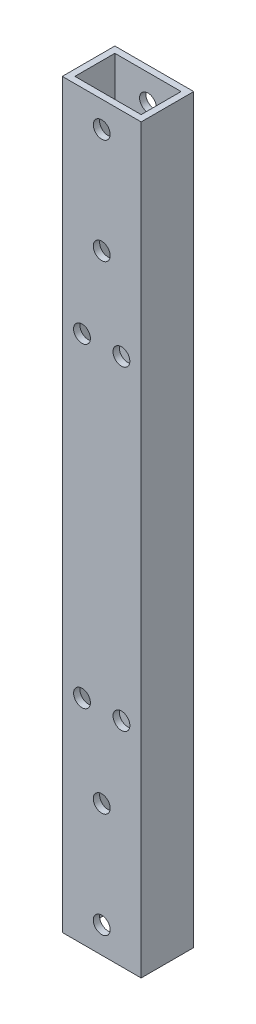
SolidWorks part; units mm, degrees
ref_plane "正面" through (0, 0, 0) normal (0, 0, 1) x (1, 0, 0)
ref_plane "平面" through (0, 0, 0) normal (0, 1, 0) x (1, 0, 0)
ref_plane "右側面" through (0, 0, 0) normal (1, 0, 0) x (0, 0, -1)
sketch "ｽｹｯﾁ1" plane through (0, 0, 0) normal (0, 1, 0) x (1, 0, 0)
  line L0 (-6.3, 3.8) -> (6.3, 3.8)
  line L1 (-7.5, 5) -> (7.5, 5)
  line L2 (-7.5, 5) -> (-7.5, -5)
  line L3 (-7.5, -5) -> (7.5, -5)
  line L4 (7.5, 5) -> (7.5, -5)
  line L5 (-7.5, 5) -> (7.5, -5) construction
  line L6 (-7.5, -5) -> (7.5, 5) construction
  line L7 (6.3, 3.8) -> (6.3, -3.8)
  line L8 (-6.3, -3.8) -> (6.3, -3.8)
  line L9 (-6.3, 3.8) -> (-6.3, -3.8)
  point P0 (0, 0)
  dimension "D1" = 15
  dimension "D2" = 10
  dimension "D3" = 1.2
extrude "ﾎﾞｽ - 押し出し1" add sketch "ｽｹｯﾁ1" along normal mid plane 141
sketch "ｽｹｯﾁ2" plane through (0, 0, -5) normal (0, 0, -1) x (-1, 0, 0)
  line L0 (0, 0) -> (-7.5, 0) construction
  line L1 (-7.5, 70.5) -> (-7.5, -70.5) construction
  line L2 (0, 0) -> (0, -70.5) construction
  line L3 (-7.5, -70.5) -> (7.5, -70.5) construction
  line L4 (0, 0) -> (0, -30) construction
  line L5 (0, -30) -> (7.5, -30) construction
  line L6 (7.5, 70.5) -> (7.5, -70.5) construction
  circle A0 centre (0, -65.5) radius 1.6
  circle A1 centre (0, -45.5) radius 1.6
  circle A2 centre (0, 45.5) radius 1.6
  circle A3 centre (0, 65.5) radius 1.6
  circle A6 centre (3.75, -30) radius 1.6
  circle A7 centre (-3.75, -30) radius 1.6
  circle A8 centre (-3.75, 30) radius 1.6
  circle A9 centre (3.75, 30) radius 1.6
  dimension "D1" = 3.2
  dimension "D2" = 3.2
  dimension "D6" = 3.2
  dimension "D3" = 5
  dimension "D4" = 20
  dimension "D5" = 30
extrude "ｶｯﾄ - 押し出し1" cut sketch "ｽｹｯﾁ2" against normal blind 100
